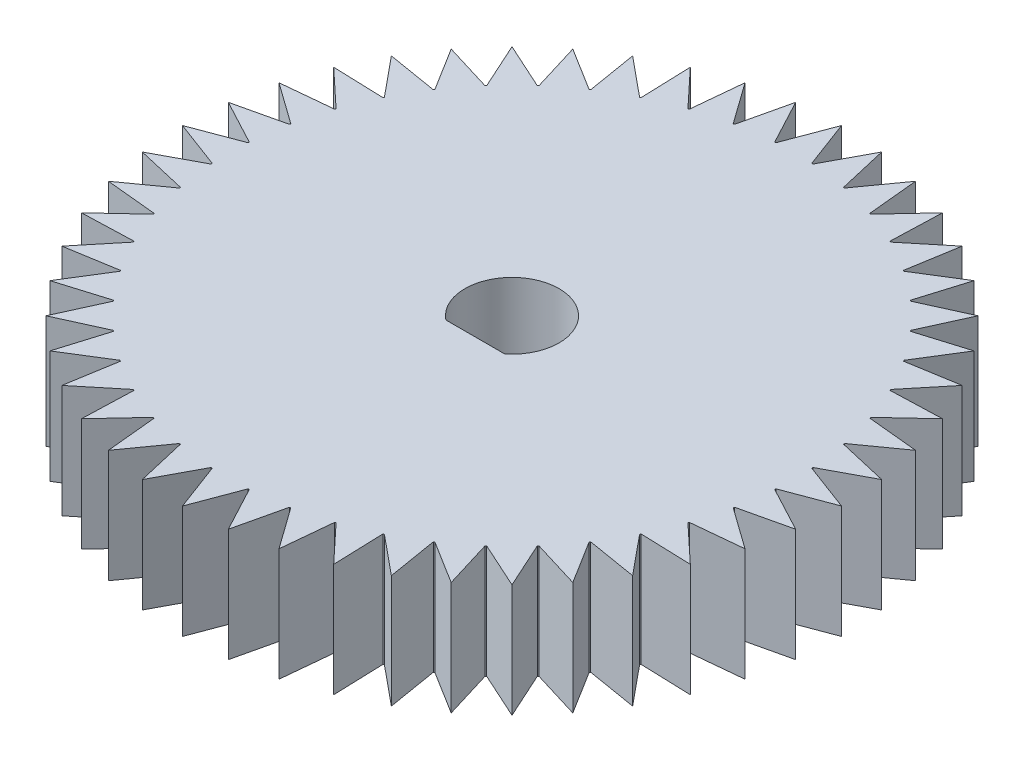
SolidWorks part; units mm, degrees
ref_plane "Спереди" through (0, 0, 0) normal (0, 0, 1) x (1, 0, 0)
ref_plane "Сверху" through (0, 0, 0) normal (0, 1, 0) x (1, 0, 0)
ref_plane "Справа" through (0, 0, 0) normal (1, 0, 0) x (0, 0, -1)
sketch "Эскиз1" plane through (0, 0, 0) normal (0, 1, 0) x (1, 0, 0)
  line L0 (2.2842, 17.3503) -> (2.8954, 14.7179)
  line L1 (1.0126, 14.9658) -> (2.2842, 17.3503)
  line L2 (4.5293, 16.9037) -> (4.7917, 14.2141)
  line L3 (2.9573, 14.7056) -> (4.5293, 16.9037)
  line L222 (-1.5644, -1.95) -> (1.5644, -1.95)
  line L299 (6.697, 16.1679) -> (6.606, 13.467)
  line L303 (4.8515, 14.1938) -> (6.697, 16.1679)
  line L304 (0, 17.5) -> (0.9495, 14.9699)
  line L305 (-0.9495, 14.9699) -> (0, 17.5)
  line L306 (8.75, 15.1554) -> (8.3073, 12.4896)
  line L307 (6.6626, 13.4391) -> (8.75, 15.1554)
  line L308 (10.6533, 13.8837) -> (9.8664, 11.2984)
  line L309 (8.3598, 12.4545) -> (10.6533, 13.8837)
  line L310 (12.3744, 12.3744) -> (11.2567, 9.9139)
  line L311 (9.9139, 11.2567) -> (12.3744, 12.3744)
  line L312 (13.8837, 10.6533) -> (12.4545, 8.3598)
  line L313 (11.2984, 9.8664) -> (13.8837, 10.6533)
  line L314 (15.1554, 8.75) -> (13.4391, 6.6626)
  line L315 (12.4896, 8.3073) -> (15.1554, 8.75)
  line L316 (16.1679, 6.697) -> (14.1938, 4.8515)
  line L317 (13.467, 6.606) -> (16.1679, 6.697)
  line L318 (16.9037, 4.5293) -> (14.7056, 2.9573)
  line L319 (14.2141, 4.7917) -> (16.9037, 4.5293)
  line L320 (17.3503, 2.2842) -> (14.9658, 1.0126)
  line L321 (14.7179, 2.8954) -> (17.3503, 2.2842)
  line L322 (17.5, 0) -> (14.9699, -0.9495)
  line L323 (14.9699, 0.9495) -> (17.5, 0)
  line L324 (17.3503, -2.2842) -> (14.7179, -2.8954)
  line L325 (14.9658, -1.0126) -> (17.3503, -2.2842)
  line L326 (16.9037, -4.5293) -> (14.2141, -4.7917)
  line L327 (14.7056, -2.9573) -> (16.9037, -4.5293)
  line L328 (16.1679, -6.697) -> (13.467, -6.606)
  line L329 (14.1938, -4.8515) -> (16.1679, -6.697)
  line L330 (15.1554, -8.75) -> (12.4896, -8.3073)
  line L331 (13.4391, -6.6626) -> (15.1554, -8.75)
  line L332 (13.8837, -10.6533) -> (11.2984, -9.8664)
  line L333 (12.4545, -8.3598) -> (13.8837, -10.6533)
  line L334 (12.3744, -12.3744) -> (9.9139, -11.2567)
  line L335 (11.2567, -9.9139) -> (12.3744, -12.3744)
  line L336 (10.6533, -13.8837) -> (8.3598, -12.4545)
  line L337 (9.8664, -11.2984) -> (10.6533, -13.8837)
  line L338 (8.75, -15.1554) -> (6.6626, -13.4391)
  line L339 (8.3073, -12.4896) -> (8.75, -15.1554)
  line L340 (6.697, -16.1679) -> (4.8515, -14.1938)
  line L341 (6.606, -13.467) -> (6.697, -16.1679)
  line L342 (4.5293, -16.9037) -> (2.9573, -14.7056)
  line L343 (4.7917, -14.2141) -> (4.5293, -16.9037)
  line L344 (2.2842, -17.3503) -> (1.0126, -14.9658)
  line L345 (2.8954, -14.7179) -> (2.2842, -17.3503)
  line L346 (0, -17.5) -> (-0.9495, -14.9699)
  line L347 (0.9495, -14.9699) -> (0, -17.5)
  line L348 (-2.2842, -17.3503) -> (-2.8954, -14.7179)
  line L349 (-1.0126, -14.9658) -> (-2.2842, -17.3503)
  line L350 (-4.5293, -16.9037) -> (-4.7917, -14.2141)
  line L351 (-2.9573, -14.7056) -> (-4.5293, -16.9037)
  line L352 (-6.697, -16.1679) -> (-6.606, -13.467)
  line L353 (-4.8515, -14.1938) -> (-6.697, -16.1679)
  line L354 (-8.75, -15.1554) -> (-8.3073, -12.4896)
  line L355 (-6.6626, -13.4391) -> (-8.75, -15.1554)
  line L356 (-10.6533, -13.8837) -> (-9.8664, -11.2984)
  line L357 (-8.3598, -12.4545) -> (-10.6533, -13.8837)
  line L358 (-12.3744, -12.3744) -> (-11.2567, -9.9139)
  line L359 (-9.9139, -11.2567) -> (-12.3744, -12.3744)
  line L360 (-13.8837, -10.6533) -> (-12.4545, -8.3598)
  line L361 (-11.2984, -9.8664) -> (-13.8837, -10.6533)
  line L362 (-15.1554, -8.75) -> (-13.4391, -6.6626)
  line L363 (-12.4896, -8.3073) -> (-15.1554, -8.75)
  line L364 (-16.1679, -6.697) -> (-14.1938, -4.8515)
  line L365 (-13.467, -6.606) -> (-16.1679, -6.697)
  line L366 (-16.9037, -4.5293) -> (-14.7056, -2.9573)
  line L367 (-14.2141, -4.7917) -> (-16.9037, -4.5293)
  line L368 (-17.3503, -2.2842) -> (-14.9658, -1.0126)
  line L369 (-14.7179, -2.8954) -> (-17.3503, -2.2842)
  line L370 (-17.5, 0) -> (-14.9699, 0.9495)
  line L371 (-14.9699, -0.9495) -> (-17.5, 0)
  line L372 (-17.3503, 2.2842) -> (-14.7179, 2.8954)
  line L373 (-14.9658, 1.0126) -> (-17.3503, 2.2842)
  line L374 (-16.9037, 4.5293) -> (-14.2141, 4.7917)
  line L375 (-14.7056, 2.9573) -> (-16.9037, 4.5293)
  line L376 (-16.1679, 6.697) -> (-13.467, 6.606)
  line L377 (-14.1938, 4.8515) -> (-16.1679, 6.697)
  line L378 (-15.1554, 8.75) -> (-12.4896, 8.3073)
  line L379 (-13.4391, 6.6626) -> (-15.1554, 8.75)
  line L380 (-13.8837, 10.6533) -> (-11.2984, 9.8664)
  line L381 (-12.4545, 8.3598) -> (-13.8837, 10.6533)
  line L382 (-12.3744, 12.3744) -> (-9.9139, 11.2567)
  line L383 (-11.2567, 9.9139) -> (-12.3744, 12.3744)
  line L384 (-10.6533, 13.8837) -> (-8.3598, 12.4545)
  line L385 (-9.8664, 11.2984) -> (-10.6533, 13.8837)
  line L386 (-8.75, 15.1554) -> (-6.6626, 13.4391)
  line L387 (-8.3073, 12.4896) -> (-8.75, 15.1554)
  line L388 (-6.697, 16.1679) -> (-4.8515, 14.1938)
  line L389 (-6.606, 13.467) -> (-6.697, 16.1679)
  line L390 (-4.5293, 16.9037) -> (-2.9573, 14.7056)
  line L391 (-4.7917, 14.2141) -> (-4.5293, 16.9037)
  line L392 (-2.2842, 17.3503) -> (-1.0126, 14.9658)
  line L393 (-2.8954, 14.7179) -> (-2.2842, 17.3503)
  circle A3 centre (0, 0) radius 15
  arc A6 (-1.5644, -1.95) -> (1.5644, -1.95) centre (0, 0) cw
  point P158 (0, 0)
  point P224 (0, 0)
extrude "Бобышка-Вытянуть5" add sketch "Эскиз1" along normal blind 6 contours A3 | A3 L344 L345 | A3 L342 L343 | A3 L340 L341 | A3 L338 L339 | A3 L336 L337 | A3 L334 L335 | A3 L346 L347 | A3 L348 L349 | A3 L350 L351 | A3 L352 L353 | A3 L354 L355 | A3 L356 L357 | A3 L358 L359 | A3 L360 L361 | A3 L362 L363 | A3 L364 L365 | A3 L366 L367 | A3 L368 L369 | A3 L370 L371 | A3 L372 L373 | A3 L374 L375 | A3 L376 L377 | A3 L378 L379 | A3 L380 L381 | A3 L382 L383 | A3 L384 L385 | A3 L386 L387 | A3 L388 L389 | A3 L390 L391 | A3 L392 L393 | A3 L304 L305 | A3 L0 L1 | A3 L2 L3 | A3 L299 L303 | A3 L306 L307 | A3 L308 L309 | A3 L310 L311 | A3 L312 L313 | A3 L314 L315 | A3 L316 L317 | A3 L318 L319 | A3 L320 L321 | A3 L322 L323 | A3 L324 L325 | A3 L326 L327 | A3 L328 L329 | A3 L330 L331 | A3 L332 L333
